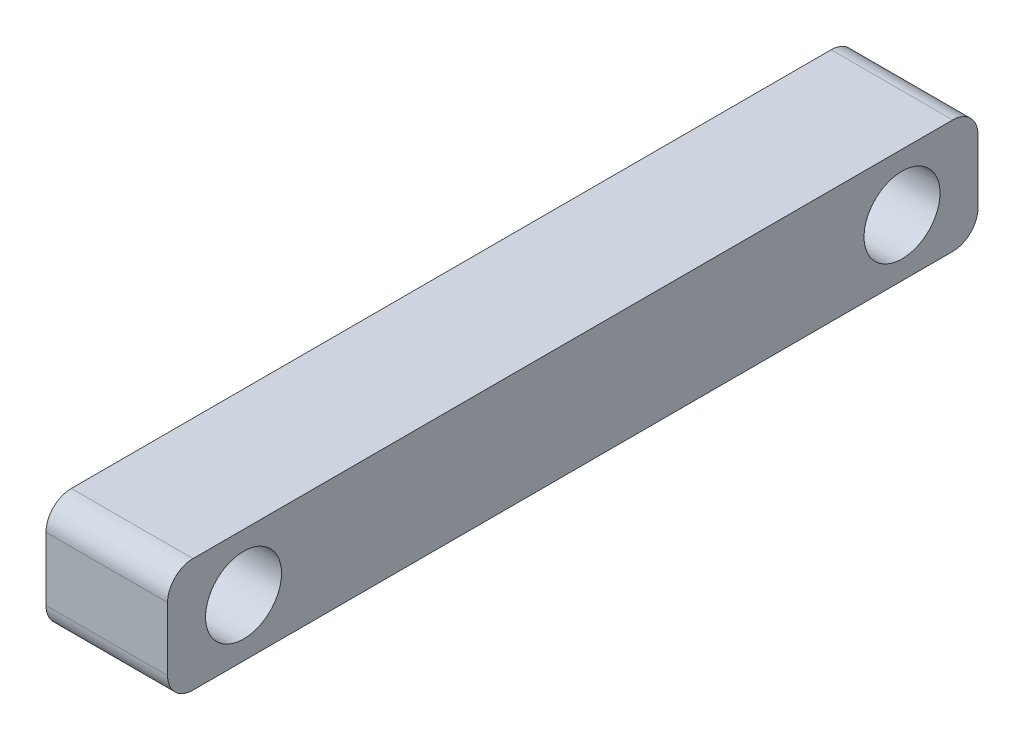
SolidWorks part; units mm, degrees
ref_plane "Alzado" through (0, 0, 0) normal (0, 0, 1) x (1, 0, 0)
ref_plane "Planta" through (0, 0, 0) normal (0, 1, 0) x (1, 0, 0)
ref_plane "Vista lateral" through (0, 0, 0) normal (1, 0, 0) x (0, 0, -1)
sketch "Croquis1" plane through (0, 0, 0) normal (1, 0, 0) x (0, 0, -1)
  line L0 (-15, 2.25) -> (15, 2.25)
  line L2 (-16, 0) -> (16, 0) construction
  line L3 (-16, 1.25) -> (-16, -1.25)
  line L4 (-15, -2.25) -> (15, -2.25)
  line L5 (16, 1.25) -> (16, -1.25)
  arc A0 (-16, -1.25) -> (-15, -2.25) centre (-15, -1.25) ccw
  arc A1 (-16, 1.25) -> (-15, 2.25) centre (-15, 1.25) cw
  arc A2 (15, -2.25) -> (16, -1.25) centre (15, -1.25) ccw
  arc A3 (15, 2.25) -> (16, 1.25) centre (15, 1.25) cw
  point P1 (0, 0)
  point P9 (-16, -2.25)
  point P13 (-16, 2.25)
  point P16 (16, -2.25)
  point P19 (16, 2.25)
  dimension "D3" = 1
  dimension "D4" = 1
  dimension "D1" = 2.25
  dimension "D2" = 32
extrude "Saliente-Extruir1" add sketch "Croquis1" along normal mid plane 4.8
sketch "Croquis2" plane through (0, 0, 0) normal (1, 0, 0) x (0, 0, -1)
  line L0 (-16, 1.25) -> (-16, -1.25) construction
  line L1 (16, -1.25) -> (16, 1.25) construction
  circle A0 centre (-13, 0) radius 1.5
  circle A1 centre (13, 0) radius 1.5
  dimension "D1" = 3
  dimension "D3" = 3
  dimension "D2" = 3
  dimension "D4" = 3
extrude "Cortar-Extruir1" cut sketch "Croquis2" against normal through all both and the other way through all
